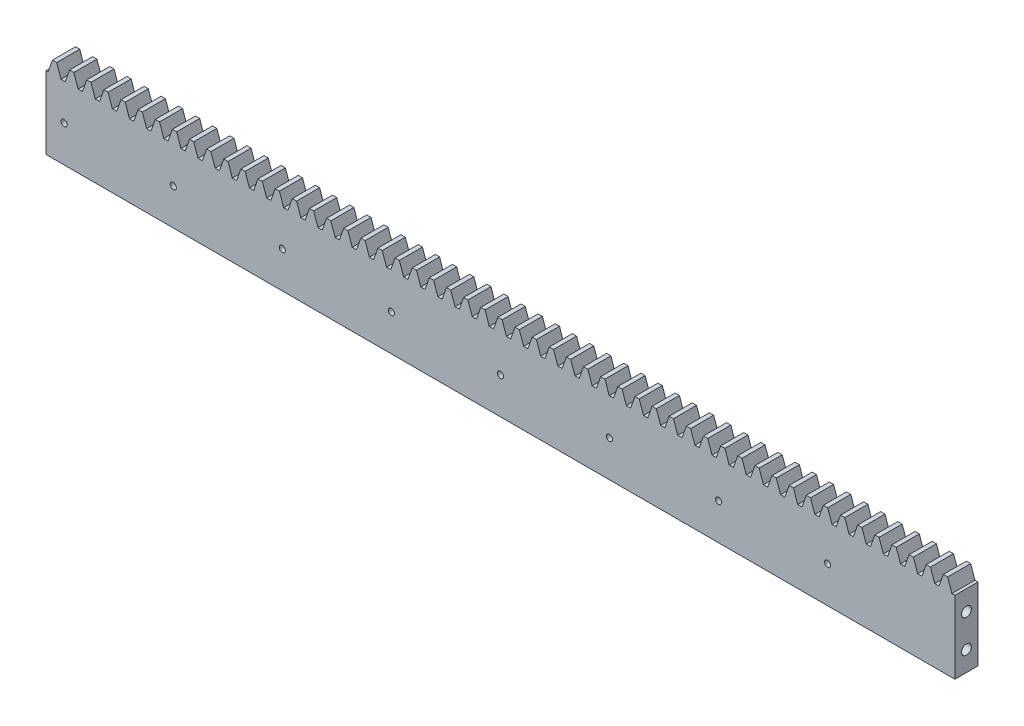
SolidWorks part; units mm, degrees
ref_plane "Front Plane" through (0, 0, 0) normal (0, 0, 1) x (1, 0, 0)
ref_plane "Top Plane" through (0, 0, 0) normal (0, 1, 0) x (1, 0, 0)
ref_plane "Right Plane" through (0, 0, 0) normal (1, 0, 0) x (0, 0, -1)
sketch "Original Sketch" plane through (0, 0, 0) normal (0, 0, 1) x (1, 0, 0)
  line L0 (5.3011, 16.625) -> (4.1236, 16.625) construction
  line L1 (4.1236, 16.625) -> (2.9446, 20) construction
  line L2 (2.9446, 20) -> (1.7677, 20) construction
  line L3 (1.7677, 20) -> (0.5887, 16.625) construction
  line L4 (0.5887, 16.625) -> (0, 16.625) construction
  line L5 (0, 16.625) -> (0, 0) construction
  line L6 (0, 0) -> (303, 0) construction
  line L7 (303, 0) -> (303, 18.9683) construction
  line L8 (303, 18.9683) -> (302.1814, 16.625) construction
  line L9 (302.1814, 16.625) -> (301.0039, 16.625) construction
  line L10 (301.0039, 16.625) -> (299.8249, 20) construction
  line L11 (299.8249, 20) -> (298.648, 20) construction
  line L12 (298.648, 20) -> (297.469, 16.625) construction
  line L13 (297.469, 16.625) -> (296.2915, 16.625) construction
  line L14 (296.2915, 16.625) -> (295.1125, 20) construction
  line L15 (295.1125, 20) -> (293.9356, 20) construction
  line L16 (293.9356, 20) -> (292.7566, 16.625) construction
  line L17 (292.7566, 16.625) -> (291.5791, 16.625) construction
  line L18 (291.5791, 16.625) -> (290.4001, 20) construction
  line L19 (290.4001, 20) -> (289.2232, 20) construction
  line L20 (289.2232, 20) -> (288.0442, 16.625) construction
  line L21 (288.0442, 16.625) -> (286.8667, 16.625) construction
  line L22 (286.8667, 16.625) -> (285.6877, 20) construction
  line L23 (285.6877, 20) -> (284.5109, 20) construction
  line L24 (284.5109, 20) -> (283.3318, 16.625) construction
  line L25 (283.3318, 16.625) -> (282.1544, 16.625) construction
  line L26 (282.1544, 16.625) -> (280.9753, 20) construction
  line L27 (280.9753, 20) -> (279.7985, 20) construction
  line L28 (279.7985, 20) -> (278.6195, 16.625) construction
  line L29 (278.6195, 16.625) -> (277.442, 16.625) construction
  line L30 (277.442, 16.625) -> (276.263, 20) construction
  line L31 (276.263, 20) -> (275.0861, 20) construction
  line L32 (275.0861, 20) -> (273.9071, 16.625) construction
  line L33 (273.9071, 16.625) -> (272.7296, 16.625) construction
  line L34 (272.7296, 16.625) -> (271.5506, 20) construction
  line L35 (271.5506, 20) -> (270.3737, 20) construction
  line L36 (270.3737, 20) -> (269.1947, 16.625) construction
  line L37 (269.1947, 16.625) -> (268.0172, 16.625) construction
  line L38 (268.0172, 16.625) -> (266.8382, 20) construction
  line L39 (266.8382, 20) -> (265.6613, 20) construction
  line L40 (265.6613, 20) -> (264.4823, 16.625) construction
  line L41 (264.4823, 16.625) -> (263.3048, 16.625) construction
  line L42 (263.3048, 16.625) -> (262.1258, 20) construction
  line L43 (262.1258, 20) -> (260.9489, 20) construction
  line L44 (260.9489, 20) -> (259.7699, 16.625) construction
  line L45 (259.7699, 16.625) -> (258.5924, 16.625) construction
  line L46 (258.5924, 16.625) -> (257.4134, 20) construction
  line L47 (257.4134, 20) -> (256.2365, 20) construction
  line L48 (256.2365, 20) -> (255.0575, 16.625) construction
  line L49 (255.0575, 16.625) -> (253.88, 16.625) construction
  line L50 (253.88, 16.625) -> (252.701, 20) construction
  line L51 (252.701, 20) -> (251.5242, 20) construction
  line L52 (251.5242, 20) -> (250.3452, 16.625) construction
  line L53 (250.3452, 16.625) -> (249.1677, 16.625) construction
  line L54 (249.1677, 16.625) -> (247.9887, 20) construction
  line L55 (247.9887, 20) -> (246.8118, 20) construction
  line L56 (246.8118, 20) -> (245.6328, 16.625) construction
  line L57 (245.6328, 16.625) -> (244.4553, 16.625) construction
  line L58 (244.4553, 16.625) -> (243.2763, 20) construction
  line L59 (243.2763, 20) -> (242.0994, 20) construction
  line L60 (242.0994, 20) -> (240.9204, 16.625) construction
  line L61 (240.9204, 16.625) -> (239.7429, 16.625) construction
  line L62 (239.7429, 16.625) -> (238.5639, 20) construction
  line L63 (238.5639, 20) -> (237.387, 20) construction
  line L64 (237.387, 20) -> (236.208, 16.625) construction
  line L65 (236.208, 16.625) -> (235.0305, 16.625) construction
  line L66 (235.0305, 16.625) -> (233.8515, 20) construction
  line L67 (233.8515, 20) -> (232.6746, 20) construction
  line L68 (232.6746, 20) -> (231.4956, 16.625) construction
  line L69 (231.4956, 16.625) -> (230.3181, 16.625) construction
  line L70 (230.3181, 16.625) -> (229.1391, 20) construction
  line L71 (229.1391, 20) -> (227.9622, 20) construction
  line L72 (227.9622, 20) -> (226.7832, 16.625) construction
  line L73 (226.7832, 16.625) -> (225.6057, 16.625) construction
  line L74 (225.6057, 16.625) -> (224.4267, 20) construction
  line L75 (224.4267, 20) -> (223.2498, 20) construction
  line L76 (223.2498, 20) -> (222.0708, 16.625) construction
  line L77 (222.0708, 16.625) -> (220.8933, 16.625) construction
  line L78 (220.8933, 16.625) -> (219.7143, 20) construction
  line L79 (219.7143, 20) -> (218.5375, 20) construction
  line L80 (218.5375, 20) -> (217.3585, 16.625) construction
  line L81 (217.3585, 16.625) -> (216.181, 16.625) construction
  line L82 (216.181, 16.625) -> (215.002, 20) construction
  line L83 (215.002, 20) -> (213.8251, 20) construction
  line L84 (213.8251, 20) -> (212.6461, 16.625) construction
  line L85 (212.6461, 16.625) -> (211.4686, 16.625) construction
  line L86 (211.4686, 16.625) -> (210.2896, 20) construction
  line L87 (210.2896, 20) -> (209.1127, 20) construction
  line L88 (209.1127, 20) -> (207.9337, 16.625) construction
  line L89 (207.9337, 16.625) -> (206.7562, 16.625) construction
  line L90 (206.7562, 16.625) -> (205.5772, 20) construction
  line L91 (205.5772, 20) -> (204.4003, 20) construction
  line L92 (204.4003, 20) -> (203.2213, 16.625) construction
  line L93 (203.2213, 16.625) -> (202.0438, 16.625) construction
  line L94 (202.0438, 16.625) -> (200.8648, 20) construction
  line L95 (200.8648, 20) -> (199.6879, 20) construction
  line L96 (199.6879, 20) -> (198.5089, 16.625) construction
  line L97 (198.5089, 16.625) -> (197.3314, 16.625) construction
  line L98 (197.3314, 16.625) -> (196.1524, 20) construction
  line L99 (196.1524, 20) -> (194.9755, 20) construction
  line L100 (194.9755, 20) -> (193.7965, 16.625) construction
  line L101 (193.7965, 16.625) -> (192.619, 16.625) construction
  line L102 (192.619, 16.625) -> (191.44, 20) construction
  line L103 (191.44, 20) -> (190.2631, 20) construction
  line L104 (190.2631, 20) -> (189.0841, 16.625) construction
  line L105 (189.0841, 16.625) -> (187.9067, 16.625) construction
  line L106 (187.9067, 16.625) -> (186.7276, 20) construction
  line L107 (186.7276, 20) -> (185.5508, 20) construction
  line L108 (185.5508, 20) -> (184.3718, 16.625) construction
  line L109 (184.3718, 16.625) -> (183.1943, 16.625) construction
  line L110 (183.1943, 16.625) -> (182.0153, 20) construction
  line L111 (182.0153, 20) -> (180.8384, 20) construction
  line L112 (180.8384, 20) -> (179.6594, 16.625) construction
  line L113 (179.6594, 16.625) -> (178.4819, 16.625) construction
  line L114 (178.4819, 16.625) -> (177.3029, 20) construction
  line L115 (177.3029, 20) -> (176.126, 20) construction
  line L116 (176.126, 20) -> (174.947, 16.625) construction
  line L117 (174.947, 16.625) -> (173.7695, 16.625) construction
  line L118 (173.7695, 16.625) -> (172.5905, 20) construction
  line L119 (172.5905, 20) -> (171.4136, 20) construction
  line L120 (171.4136, 20) -> (170.2346, 16.625) construction
  line L121 (170.2346, 16.625) -> (169.0571, 16.625) construction
  line L122 (169.0571, 16.625) -> (167.8781, 20) construction
  line L123 (167.8781, 20) -> (166.7012, 20) construction
  line L124 (166.7012, 20) -> (165.5222, 16.625) construction
  line L125 (165.5222, 16.625) -> (164.3447, 16.625) construction
  line L126 (164.3447, 16.625) -> (163.1657, 20) construction
  line L127 (163.1657, 20) -> (161.9888, 20) construction
  line L128 (161.9888, 20) -> (160.8098, 16.625) construction
  line L129 (160.8098, 16.625) -> (159.6323, 16.625) construction
  line L130 (159.6323, 16.625) -> (158.4533, 20) construction
  line L131 (158.4533, 20) -> (157.2765, 20) construction
  line L132 (157.2765, 20) -> (156.0975, 16.625) construction
  line L133 (156.0975, 16.625) -> (154.92, 16.625) construction
  line L134 (154.92, 16.625) -> (153.741, 20) construction
  line L135 (153.741, 20) -> (152.5641, 20) construction
  line L136 (152.5641, 20) -> (151.3851, 16.625) construction
  line L137 (151.3851, 16.625) -> (150.2076, 16.625) construction
  line L138 (150.2076, 16.625) -> (149.0286, 20) construction
  line L139 (149.0286, 20) -> (147.8517, 20) construction
  line L140 (147.8517, 20) -> (146.6727, 16.625) construction
  line L141 (146.6727, 16.625) -> (145.4952, 16.625) construction
  line L142 (145.4952, 16.625) -> (144.3162, 20) construction
  line L143 (144.3162, 20) -> (143.1393, 20) construction
  line L144 (143.1393, 20) -> (141.9603, 16.625) construction
  line L145 (141.9603, 16.625) -> (140.7828, 16.625) construction
  line L146 (140.7828, 16.625) -> (139.6038, 20) construction
  line L147 (139.6038, 20) -> (138.4269, 20) construction
  line L148 (138.4269, 20) -> (137.2479, 16.625) construction
  line L149 (137.2479, 16.625) -> (136.0704, 16.625) construction
  line L150 (136.0704, 16.625) -> (134.8914, 20) construction
  line L151 (134.8914, 20) -> (133.7145, 20) construction
  line L152 (133.7145, 20) -> (132.5355, 16.625) construction
  line L153 (132.5355, 16.625) -> (131.358, 16.625) construction
  line L154 (131.358, 16.625) -> (130.179, 20) construction
  line L155 (130.179, 20) -> (129.0021, 20) construction
  line L156 (129.0021, 20) -> (127.8231, 16.625) construction
  line L157 (127.8231, 16.625) -> (126.6456, 16.625) construction
  line L158 (126.6456, 16.625) -> (125.4666, 20) construction
  line L159 (125.4666, 20) -> (124.2898, 20) construction
  line L160 (124.2898, 20) -> (123.1108, 16.625) construction
  line L161 (123.1108, 16.625) -> (121.9333, 16.625) construction
  line L162 (121.9333, 16.625) -> (120.7543, 20) construction
  line L163 (120.7543, 20) -> (119.5774, 20) construction
  line L164 (119.5774, 20) -> (118.3984, 16.625) construction
  line L165 (118.3984, 16.625) -> (117.2209, 16.625) construction
  line L166 (117.2209, 16.625) -> (116.0419, 20) construction
  line L167 (116.0419, 20) -> (114.865, 20) construction
  line L168 (114.865, 20) -> (113.686, 16.625) construction
  line L169 (113.686, 16.625) -> (112.5085, 16.625) construction
  line L170 (112.5085, 16.625) -> (111.3295, 20) construction
  line L171 (111.3295, 20) -> (110.1526, 20) construction
  line L172 (110.1526, 20) -> (108.9736, 16.625) construction
  line L173 (108.9736, 16.625) -> (107.7961, 16.625) construction
  line L174 (107.7961, 16.625) -> (106.6171, 20) construction
  line L175 (106.6171, 20) -> (105.4402, 20) construction
  line L176 (105.4402, 20) -> (104.2612, 16.625) construction
  line L177 (104.2612, 16.625) -> (103.0837, 16.625) construction
  line L178 (103.0837, 16.625) -> (101.9047, 20) construction
  line L179 (101.9047, 20) -> (100.7278, 20) construction
  line L180 (100.7278, 20) -> (99.5488, 16.625) construction
  line L181 (99.5488, 16.625) -> (98.3713, 16.625) construction
  line L182 (98.3713, 16.625) -> (97.1923, 20) construction
  line L183 (97.1923, 20) -> (96.0155, 20) construction
  line L184 (96.0155, 20) -> (94.8364, 16.625) construction
  line L185 (94.8364, 16.625) -> (93.659, 16.625) construction
  line L186 (93.659, 16.625) -> (92.48, 20) construction
  line L187 (92.48, 20) -> (91.3031, 20) construction
  line L188 (91.3031, 20) -> (90.1241, 16.625) construction
  line L189 (90.1241, 16.625) -> (88.9466, 16.625) construction
  line L190 (88.9466, 16.625) -> (87.7676, 20) construction
  line L191 (87.7676, 20) -> (86.5907, 20) construction
  line L192 (86.5907, 20) -> (85.4117, 16.625) construction
  line L193 (85.4117, 16.625) -> (84.2342, 16.625) construction
  line L194 (84.2342, 16.625) -> (83.0552, 20) construction
  line L195 (83.0552, 20) -> (81.8783, 20) construction
  line L196 (81.8783, 20) -> (80.6993, 16.625) construction
  line L197 (80.6993, 16.625) -> (79.5218, 16.625) construction
  line L198 (79.5218, 16.625) -> (78.3428, 20) construction
  line L199 (78.3428, 20) -> (77.1659, 20) construction
  line L200 (77.1659, 20) -> (75.9869, 16.625) construction
  line L201 (75.9869, 16.625) -> (74.8094, 16.625) construction
  line L202 (74.8094, 16.625) -> (73.6304, 20) construction
  line L203 (73.6304, 20) -> (72.4535, 20) construction
  line L204 (72.4535, 20) -> (71.2745, 16.625) construction
  line L205 (71.2745, 16.625) -> (70.097, 16.625) construction
  line L206 (70.097, 16.625) -> (68.918, 20) construction
  line L207 (68.918, 20) -> (67.7411, 20) construction
  line L208 (67.7411, 20) -> (66.5621, 16.625) construction
  line L209 (66.5621, 16.625) -> (65.3846, 16.625) construction
  line L210 (65.3846, 16.625) -> (64.2056, 20) construction
  line L211 (64.2056, 20) -> (63.0288, 20) construction
  line L212 (63.0288, 20) -> (61.8498, 16.625) construction
  line L213 (61.8498, 16.625) -> (60.6723, 16.625) construction
  line L214 (60.6723, 16.625) -> (59.4933, 20) construction
  line L215 (59.4933, 20) -> (58.3164, 20) construction
  line L216 (58.3164, 20) -> (57.1374, 16.625) construction
  line L217 (57.1374, 16.625) -> (55.9599, 16.625) construction
  line L218 (55.9599, 16.625) -> (54.7809, 20) construction
  line L219 (54.7809, 20) -> (53.604, 20) construction
  line L220 (53.604, 20) -> (52.425, 16.625) construction
  line L221 (52.425, 16.625) -> (51.2475, 16.625) construction
  line L222 (51.2475, 16.625) -> (50.0685, 20) construction
  line L223 (50.0685, 20) -> (48.8916, 20) construction
  line L224 (48.8916, 20) -> (47.7126, 16.625) construction
  line L225 (47.7126, 16.625) -> (46.5351, 16.625) construction
  line L226 (46.5351, 16.625) -> (45.3561, 20) construction
  line L227 (45.3561, 20) -> (44.1792, 20) construction
  line L228 (44.1792, 20) -> (43.0002, 16.625) construction
  line L229 (43.0002, 16.625) -> (41.8227, 16.625) construction
  line L230 (41.8227, 16.625) -> (40.6437, 20) construction
  line L231 (40.6437, 20) -> (39.4668, 20) construction
  line L232 (39.4668, 20) -> (38.2878, 16.625) construction
  line L233 (38.2878, 16.625) -> (37.1103, 16.625) construction
  line L234 (37.1103, 16.625) -> (35.9313, 20) construction
  line L235 (35.9313, 20) -> (34.7544, 20) construction
  line L236 (34.7544, 20) -> (33.5754, 16.625) construction
  line L237 (33.5754, 16.625) -> (32.3979, 16.625) construction
  line L238 (32.3979, 16.625) -> (31.2189, 20) construction
  line L239 (31.2189, 20) -> (30.0421, 20) construction
  line L240 (30.0421, 20) -> (28.8631, 16.625) construction
  line L241 (28.8631, 16.625) -> (27.6856, 16.625) construction
  line L242 (27.6856, 16.625) -> (26.5066, 20) construction
  line L243 (26.5066, 20) -> (25.3297, 20) construction
  line L244 (25.3297, 20) -> (24.1507, 16.625) construction
  line L245 (24.1507, 16.625) -> (22.9732, 16.625) construction
  line L246 (22.9732, 16.625) -> (21.7942, 20) construction
  line L247 (21.7942, 20) -> (20.6173, 20) construction
  line L248 (20.6173, 20) -> (19.4383, 16.625) construction
  line L249 (19.4383, 16.625) -> (18.2608, 16.625) construction
  line L250 (18.2608, 16.625) -> (17.0818, 20) construction
  line L251 (17.0818, 20) -> (15.9049, 20) construction
  line L252 (15.9049, 20) -> (14.7259, 16.625) construction
  line L253 (14.7259, 16.625) -> (13.5484, 16.625) construction
  line L254 (13.5484, 16.625) -> (12.3694, 20) construction
  line L255 (12.3694, 20) -> (11.1925, 20) construction
  line L256 (11.1925, 20) -> (10.0135, 16.625) construction
  line L257 (10.0135, 16.625) -> (8.836, 16.625) construction
  line L258 (8.836, 16.625) -> (7.657, 20) construction
  line L259 (7.657, 20) -> (6.4801, 20) construction
  line L260 (6.4801, 20) -> (5.3011, 16.625) construction
sketch "Sketch6" plane through (0, 0, 0) normal (0, 0, 1) x (1, 0, 0)
  line L2 (303, 0) -> (303, 18.9683) construction
  line L3 (303, 18.9683) -> (302.1814, 16.625) construction
  line L4 (302.1814, 16.625) -> (301.0039, 16.625) construction
  line L5 (301.0039, 16.625) -> (299.8249, 20) construction
  line L6 (299.8249, 20) -> (298.648, 20) construction
  line L7 (298.648, 20) -> (297.469, 16.625) construction
  line L8 (297.469, 16.625) -> (296.2915, 16.625) construction
  line L9 (296.2915, 16.625) -> (295.1125, 20) construction
  line L10 (295.1125, 20) -> (293.9356, 20) construction
  line L11 (293.9356, 20) -> (292.7566, 16.625) construction
  line L12 (292.7566, 16.625) -> (291.5791, 16.625) construction
  line L13 (291.5791, 16.625) -> (290.4001, 20) construction
  line L14 (290.4001, 20) -> (289.2232, 20) construction
  line L15 (289.2232, 20) -> (288.0442, 16.625) construction
  line L16 (288.0442, 16.625) -> (286.8667, 16.625) construction
  line L17 (286.8667, 16.625) -> (285.6877, 20) construction
  line L18 (285.6877, 20) -> (284.5109, 20) construction
  line L19 (284.5109, 20) -> (283.3318, 16.625) construction
  line L20 (283.3318, 16.625) -> (282.1544, 16.625) construction
  line L21 (282.1544, 16.625) -> (280.9753, 20) construction
  line L22 (280.9753, 20) -> (279.7985, 20) construction
  line L23 (279.7985, 20) -> (278.6195, 16.625) construction
  line L24 (278.6195, 16.625) -> (277.442, 16.625) construction
  line L25 (277.442, 16.625) -> (276.263, 20) construction
  line L26 (276.263, 20) -> (275.0861, 20) construction
  line L27 (275.0861, 20) -> (273.9071, 16.625) construction
  line L28 (273.9071, 16.625) -> (272.7296, 16.625) construction
  line L29 (272.7296, 16.625) -> (271.5506, 20) construction
  line L30 (271.5506, 20) -> (270.3737, 20) construction
  line L31 (270.3737, 20) -> (269.1947, 16.625) construction
  line L32 (269.1947, 16.625) -> (268.0172, 16.625) construction
  line L33 (268.0172, 16.625) -> (266.8382, 20) construction
  line L34 (266.8382, 20) -> (265.6613, 20) construction
  line L35 (265.6613, 20) -> (264.4823, 16.625) construction
  line L36 (264.4823, 16.625) -> (263.3048, 16.625) construction
  line L37 (263.3048, 16.625) -> (262.1258, 20) construction
  line L38 (262.1258, 20) -> (260.9489, 20) construction
  line L39 (260.9489, 20) -> (259.7699, 16.625) construction
  line L40 (259.7699, 16.625) -> (258.5924, 16.625) construction
  line L41 (258.5924, 16.625) -> (257.4134, 20) construction
  line L42 (257.4134, 20) -> (256.2365, 20) construction
  line L43 (256.2365, 20) -> (255.0575, 16.625) construction
  line L44 (255.0575, 16.625) -> (253.88, 16.625) construction
  line L45 (253.88, 16.625) -> (252.701, 20) construction
  line L46 (252.701, 20) -> (251.5242, 20) construction
  line L47 (251.5242, 20) -> (250.3452, 16.625) construction
  line L48 (250.3452, 16.625) -> (249.1677, 16.625) construction
  line L49 (249.1677, 16.625) -> (247.9887, 20) construction
  line L50 (247.9887, 20) -> (246.8118, 20) construction
  line L51 (246.8118, 20) -> (245.6328, 16.625) construction
  line L52 (245.6328, 16.625) -> (244.4553, 16.625) construction
  line L53 (244.4553, 16.625) -> (243.2763, 20) construction
  line L54 (243.2763, 20) -> (242.0994, 20) construction
  line L55 (242.0994, 20) -> (240.9204, 16.625) construction
  line L56 (240.9204, 16.625) -> (239.7429, 16.625) construction
  line L57 (239.7429, 16.625) -> (238.5639, 20) construction
  line L58 (238.5639, 20) -> (237.387, 20) construction
  line L59 (237.387, 20) -> (236.208, 16.625) construction
  line L60 (236.208, 16.625) -> (235.0305, 16.625) construction
  line L61 (235.0305, 16.625) -> (233.8515, 20) construction
  line L62 (233.8515, 20) -> (232.6746, 20) construction
  line L63 (232.6746, 20) -> (231.4956, 16.625) construction
  line L64 (231.4956, 16.625) -> (230.3181, 16.625) construction
  line L65 (230.3181, 16.625) -> (229.1391, 20) construction
  line L66 (229.1391, 20) -> (227.9622, 20) construction
  line L67 (227.9622, 20) -> (226.7832, 16.625) construction
  line L68 (226.7832, 16.625) -> (225.6057, 16.625) construction
  line L69 (225.6057, 16.625) -> (224.4267, 20) construction
  line L70 (224.4267, 20) -> (223.2498, 20) construction
  line L71 (223.2498, 20) -> (222.0708, 16.625) construction
  line L72 (222.0708, 16.625) -> (220.8933, 16.625) construction
  line L73 (220.8933, 16.625) -> (219.7143, 20) construction
  line L74 (219.7143, 20) -> (218.5375, 20) construction
  line L75 (218.5375, 20) -> (217.3585, 16.625) construction
  line L76 (217.3585, 16.625) -> (216.181, 16.625) construction
  line L77 (216.181, 16.625) -> (215.002, 20) construction
  line L78 (215.002, 20) -> (213.8251, 20) construction
  line L79 (213.8251, 20) -> (212.6461, 16.625) construction
  line L80 (212.6461, 16.625) -> (211.4686, 16.625) construction
  line L81 (211.4686, 16.625) -> (210.2896, 20) construction
  line L82 (210.2896, 20) -> (209.1127, 20) construction
  line L83 (209.1127, 20) -> (207.9337, 16.625) construction
  line L84 (207.9337, 16.625) -> (206.7562, 16.625) construction
  line L85 (206.7562, 16.625) -> (205.5772, 20) construction
  line L86 (205.5772, 20) -> (204.4003, 20) construction
  line L87 (204.4003, 20) -> (203.2213, 16.625) construction
  line L88 (203.2213, 16.625) -> (202.0438, 16.625) construction
  line L89 (202.0438, 16.625) -> (200.8648, 20) construction
  line L90 (200.8648, 20) -> (199.6879, 20) construction
  line L91 (199.6879, 20) -> (198.5089, 16.625) construction
  line L92 (198.5089, 16.625) -> (197.3314, 16.625) construction
  line L93 (197.3314, 16.625) -> (196.1524, 20) construction
  line L94 (196.1524, 20) -> (194.9755, 20) construction
  line L95 (194.9755, 20) -> (193.7965, 16.625) construction
  line L96 (193.7965, 16.625) -> (192.619, 16.625) construction
  line L97 (192.619, 16.625) -> (191.44, 20) construction
  line L98 (191.44, 20) -> (190.2631, 20) construction
  line L99 (190.2631, 20) -> (189.0841, 16.625) construction
  line L100 (189.0841, 16.625) -> (187.9067, 16.625) construction
  line L101 (187.9067, 16.625) -> (186.7276, 20) construction
  line L102 (186.7276, 20) -> (185.5508, 20) construction
  line L103 (185.5508, 20) -> (184.3718, 16.625) construction
  line L104 (184.3718, 16.625) -> (183.1943, 16.625) construction
  line L105 (183.1943, 16.625) -> (182.0153, 20) construction
  line L106 (182.0153, 20) -> (180.8384, 20) construction
  line L107 (180.8384, 20) -> (179.6594, 16.625) construction
  line L108 (179.6594, 16.625) -> (178.4819, 16.625) construction
  line L109 (178.4819, 16.625) -> (177.3029, 20) construction
  line L110 (177.3029, 20) -> (176.126, 20) construction
  line L111 (176.126, 20) -> (174.947, 16.625) construction
  line L112 (174.947, 16.625) -> (173.7695, 16.625) construction
  line L113 (173.7695, 16.625) -> (172.5905, 20) construction
  line L114 (172.5905, 20) -> (171.4136, 20) construction
  line L115 (171.4136, 20) -> (170.2346, 16.625) construction
  line L116 (170.2346, 16.625) -> (169.0571, 16.625) construction
  line L117 (169.0571, 16.625) -> (167.8781, 20) construction
  line L118 (167.8781, 20) -> (166.7012, 20) construction
  line L119 (166.7012, 20) -> (165.5222, 16.625) construction
  line L120 (165.5222, 16.625) -> (164.3447, 16.625) construction
  line L121 (164.3447, 16.625) -> (163.1657, 20) construction
  line L122 (163.1657, 20) -> (161.9888, 20) construction
  line L123 (161.9888, 20) -> (160.8098, 16.625) construction
  line L124 (160.8098, 16.625) -> (159.6323, 16.625) construction
  line L125 (159.6323, 16.625) -> (158.4533, 20) construction
  line L126 (158.4533, 20) -> (157.2765, 20) construction
  line L127 (157.2765, 20) -> (156.0975, 16.625) construction
  line L128 (156.0975, 16.625) -> (154.92, 16.625) construction
  line L129 (154.92, 16.625) -> (153.741, 20) construction
  line L130 (153.741, 20) -> (152.5641, 20) construction
  line L131 (152.5641, 20) -> (151.3851, 16.625) construction
  line L132 (151.3851, 16.625) -> (150.2076, 16.625) construction
  line L133 (150.2076, 16.625) -> (149.0286, 20) construction
  line L134 (149.0286, 20) -> (147.8517, 20) construction
  line L135 (147.8517, 20) -> (146.6727, 16.625) construction
  line L136 (146.6727, 16.625) -> (145.4952, 16.625) construction
  line L137 (145.4952, 16.625) -> (144.3162, 20) construction
  line L138 (144.3162, 20) -> (143.1393, 20) construction
  line L139 (143.1393, 20) -> (141.9603, 16.625) construction
  line L140 (141.9603, 16.625) -> (140.7828, 16.625) construction
  line L141 (140.7828, 16.625) -> (139.6038, 20) construction
  line L142 (139.6038, 20) -> (138.4269, 20) construction
  line L143 (138.4269, 20) -> (137.2479, 16.625) construction
  line L144 (137.2479, 16.625) -> (136.0704, 16.625) construction
  line L145 (136.0704, 16.625) -> (134.8914, 20) construction
  line L146 (134.8914, 20) -> (133.7145, 20) construction
  line L147 (133.7145, 20) -> (132.5355, 16.625) construction
  line L148 (132.5355, 16.625) -> (131.358, 16.625) construction
  line L149 (131.358, 16.625) -> (130.179, 20) construction
  line L150 (130.179, 20) -> (129.0021, 20) construction
  line L151 (129.0021, 20) -> (127.8231, 16.625) construction
  line L152 (127.8231, 16.625) -> (126.6456, 16.625) construction
  line L153 (126.6456, 16.625) -> (125.4666, 20) construction
  line L154 (125.4666, 20) -> (124.2898, 20) construction
  line L155 (124.2898, 20) -> (123.1108, 16.625) construction
  line L156 (123.1108, 16.625) -> (121.9333, 16.625) construction
  line L157 (121.9333, 16.625) -> (120.7543, 20) construction
  line L158 (120.7543, 20) -> (119.5774, 20) construction
  line L159 (119.5774, 20) -> (118.3984, 16.625) construction
  line L160 (118.3984, 16.625) -> (117.2209, 16.625) construction
  line L161 (117.2209, 16.625) -> (116.0419, 20) construction
  line L162 (116.0419, 20) -> (114.865, 20) construction
  line L163 (114.865, 20) -> (113.686, 16.625) construction
  line L164 (113.686, 16.625) -> (112.5085, 16.625) construction
  line L165 (112.5085, 16.625) -> (111.3295, 20) construction
  line L166 (111.3295, 20) -> (110.1526, 20) construction
  line L167 (110.1526, 20) -> (108.9736, 16.625) construction
  line L168 (108.9736, 16.625) -> (107.7961, 16.625) construction
  line L169 (107.7961, 16.625) -> (106.6171, 20) construction
  line L170 (106.6171, 20) -> (105.4402, 20) construction
  line L171 (105.4402, 20) -> (104.2612, 16.625) construction
  line L172 (104.2612, 16.625) -> (103.0837, 16.625) construction
  line L173 (103.0837, 16.625) -> (101.9047, 20) construction
  line L174 (101.9047, 20) -> (100.7278, 20) construction
  line L175 (100.7278, 20) -> (99.5488, 16.625) construction
  line L176 (99.5488, 16.625) -> (98.3713, 16.625) construction
  line L177 (98.3713, 16.625) -> (97.1923, 20) construction
  line L178 (97.1923, 20) -> (96.0155, 20) construction
  line L179 (96.0155, 20) -> (94.8364, 16.625) construction
  line L180 (94.8364, 16.625) -> (93.659, 16.625) construction
  line L181 (93.659, 16.625) -> (92.48, 20) construction
  line L182 (92.48, 20) -> (91.3031, 20) construction
  line L183 (91.3031, 20) -> (90.1241, 16.625) construction
  line L184 (90.1241, 16.625) -> (88.9466, 16.625) construction
  line L185 (88.9466, 16.625) -> (87.7676, 20) construction
  line L186 (87.7676, 20) -> (86.5907, 20) construction
  line L187 (86.5907, 20) -> (85.4117, 16.625) construction
  line L188 (85.4117, 16.625) -> (84.2342, 16.625) construction
  line L189 (84.2342, 16.625) -> (83.0552, 20) construction
  line L190 (83.0552, 20) -> (81.8783, 20) construction
  line L191 (81.8783, 20) -> (80.6993, 16.625) construction
  line L192 (80.6993, 16.625) -> (79.5218, 16.625) construction
  line L193 (79.5218, 16.625) -> (78.3428, 20) construction
  line L194 (78.3428, 20) -> (77.1659, 20) construction
  line L195 (77.1659, 20) -> (75.9869, 16.625) construction
  line L196 (75.9869, 16.625) -> (74.8094, 16.625) construction
  line L197 (74.8094, 16.625) -> (73.6304, 20) construction
  line L198 (73.6304, 20) -> (72.4535, 20) construction
  line L199 (72.4535, 20) -> (71.2745, 16.625) construction
  line L200 (71.2745, 16.625) -> (70.097, 16.625) construction
  line L201 (70.097, 16.625) -> (68.918, 20) construction
  line L202 (68.918, 20) -> (67.7411, 20) construction
  line L203 (67.7411, 20) -> (66.5621, 16.625) construction
  line L204 (66.5621, 16.625) -> (65.3846, 16.625) construction
  line L205 (65.3846, 16.625) -> (64.2056, 20) construction
  line L206 (64.2056, 20) -> (63.0288, 20) construction
  line L207 (63.0288, 20) -> (61.8498, 16.625) construction
  line L208 (61.8498, 16.625) -> (60.6723, 16.625) construction
  line L209 (60.6723, 16.625) -> (59.4933, 20) construction
  line L210 (59.4933, 20) -> (58.3164, 20) construction
  line L211 (58.3164, 20) -> (57.1374, 16.625) construction
  line L212 (57.1374, 16.625) -> (55.9599, 16.625) construction
  line L213 (55.9599, 16.625) -> (54.7809, 20) construction
  line L214 (54.7809, 20) -> (53.604, 20) construction
  line L215 (53.604, 20) -> (52.425, 16.625) construction
  line L216 (52.425, 16.625) -> (51.2475, 16.625) construction
  line L217 (51.2475, 16.625) -> (50.0685, 20) construction
  line L218 (50.0685, 20) -> (48.8916, 20) construction
  line L219 (48.8916, 20) -> (47.7126, 16.625) construction
  line L220 (47.7126, 16.625) -> (46.5351, 16.625) construction
  line L221 (46.5351, 16.625) -> (45.3561, 20) construction
  line L222 (45.3561, 20) -> (44.1792, 20) construction
  line L223 (44.1792, 20) -> (43.0002, 16.625) construction
  line L224 (43.0002, 16.625) -> (41.8227, 16.625) construction
  line L225 (41.8227, 16.625) -> (40.6437, 20) construction
  line L226 (40.6437, 20) -> (39.4668, 20) construction
  line L227 (39.4668, 20) -> (38.2878, 16.625) construction
  line L228 (38.2878, 16.625) -> (37.1103, 16.625) construction
  line L229 (37.1103, 16.625) -> (35.9313, 20) construction
  line L230 (35.9313, 20) -> (34.7544, 20) construction
  line L231 (34.7544, 20) -> (33.5754, 16.625) construction
  line L232 (33.5754, 16.625) -> (32.3979, 16.625) construction
  line L233 (32.3979, 16.625) -> (31.2189, 20) construction
  line L234 (31.2189, 20) -> (30.0421, 20) construction
  line L235 (30.0421, 20) -> (28.8631, 16.625) construction
  line L236 (28.8631, 16.625) -> (27.6856, 16.625) construction
  line L237 (27.6856, 16.625) -> (26.5066, 20) construction
  line L238 (26.5066, 20) -> (25.3297, 20) construction
  line L239 (25.3297, 20) -> (24.1507, 16.625) construction
  line L240 (24.1507, 16.625) -> (22.9732, 16.625) construction
  line L241 (22.9732, 16.625) -> (21.7942, 20) construction
  line L242 (21.7942, 20) -> (20.6173, 20) construction
  line L243 (20.6173, 20) -> (19.4383, 16.625) construction
  line L244 (19.4383, 16.625) -> (18.2608, 16.625) construction
  line L245 (18.2608, 16.625) -> (17.0818, 20) construction
  line L246 (17.0818, 20) -> (15.9049, 20) construction
  line L247 (15.9049, 20) -> (14.7259, 16.625) construction
  line L248 (14.7259, 16.625) -> (13.5484, 16.625) construction
  line L249 (13.5484, 16.625) -> (12.3694, 20) construction
  line L250 (12.3694, 20) -> (11.1925, 20) construction
  line L251 (11.1925, 20) -> (10.0135, 16.625) construction
  line L252 (10.0135, 16.625) -> (8.836, 16.625) construction
  line L253 (8.836, 16.625) -> (7.657, 20) construction
  line L254 (7.657, 20) -> (6.4801, 20) construction
  line L255 (6.4801, 20) -> (5.3011, 16.625) construction
  line L256 (5.3011, 16.625) -> (4.1236, 16.625) construction
  line L257 (4.1236, 16.625) -> (2.9446, 20) construction
  line L258 (2.9446, 20) -> (1.7677, 20) construction
  line L259 (1.7677, 20) -> (0.5887, 16.625) construction
  line L260 (0.5887, 16.625) -> (0, 16.625) construction
  line L263 (303, 0) -> (303, 18.9683)
  line L264 (303, 18.9683) -> (302.1814, 16.625)
  line L265 (302.1814, 16.625) -> (301.0039, 16.625)
  line L266 (301.0039, 16.625) -> (299.8249, 20)
  line L267 (299.8249, 20) -> (298.648, 20)
  line L268 (298.648, 20) -> (297.469, 16.625)
  line L269 (297.469, 16.625) -> (296.2915, 16.625)
  line L270 (296.2915, 16.625) -> (295.1125, 20)
  line L271 (295.1125, 20) -> (293.9356, 20)
  line L272 (293.9356, 20) -> (292.7566, 16.625)
  line L273 (292.7566, 16.625) -> (291.5791, 16.625)
  line L274 (291.5791, 16.625) -> (290.4001, 20)
  line L275 (290.4001, 20) -> (289.2232, 20)
  line L276 (289.2232, 20) -> (288.0442, 16.625)
  line L277 (288.0442, 16.625) -> (286.8667, 16.625)
  line L278 (286.8667, 16.625) -> (285.6877, 20)
  line L279 (285.6877, 20) -> (284.5109, 20)
  line L280 (284.5109, 20) -> (283.3318, 16.625)
  line L281 (283.3318, 16.625) -> (282.1544, 16.625)
  line L282 (282.1544, 16.625) -> (280.9753, 20)
  line L283 (280.9753, 20) -> (279.7985, 20)
  line L284 (279.7985, 20) -> (278.6195, 16.625)
  line L285 (278.6195, 16.625) -> (277.442, 16.625)
  line L286 (277.442, 16.625) -> (276.263, 20)
  line L287 (276.263, 20) -> (275.0861, 20)
  line L288 (275.0861, 20) -> (273.9071, 16.625)
  line L289 (273.9071, 16.625) -> (272.7296, 16.625)
  line L290 (272.7296, 16.625) -> (271.5506, 20)
  line L291 (271.5506, 20) -> (270.3737, 20)
  line L292 (270.3737, 20) -> (269.1947, 16.625)
  line L293 (269.1947, 16.625) -> (268.0172, 16.625)
  line L294 (268.0172, 16.625) -> (266.8382, 20)
  line L295 (266.8382, 20) -> (265.6613, 20)
  line L296 (265.6613, 20) -> (264.4823, 16.625)
  line L297 (264.4823, 16.625) -> (263.3048, 16.625)
  line L298 (263.3048, 16.625) -> (262.1258, 20)
  line L299 (262.1258, 20) -> (260.9489, 20)
  line L300 (260.9489, 20) -> (259.7699, 16.625)
  line L301 (259.7699, 16.625) -> (258.5924, 16.625)
  line L302 (258.5924, 16.625) -> (257.4134, 20)
  line L303 (257.4134, 20) -> (256.2365, 20)
  line L304 (256.2365, 20) -> (255.0575, 16.625)
  line L305 (255.0575, 16.625) -> (253.88, 16.625)
  line L306 (253.88, 16.625) -> (252.701, 20)
  line L307 (252.701, 20) -> (251.5242, 20)
  line L308 (251.5242, 20) -> (250.3452, 16.625)
  line L309 (250.3452, 16.625) -> (249.1677, 16.625)
  line L310 (249.1677, 16.625) -> (247.9887, 20)
  line L311 (247.9887, 20) -> (246.8118, 20)
  line L312 (246.8118, 20) -> (245.6328, 16.625)
  line L313 (245.6328, 16.625) -> (244.4553, 16.625)
  line L314 (244.4553, 16.625) -> (243.2763, 20)
  line L315 (243.2763, 20) -> (242.0994, 20)
  line L316 (242.0994, 20) -> (240.9204, 16.625)
  line L317 (240.9204, 16.625) -> (239.7429, 16.625)
  line L318 (239.7429, 16.625) -> (238.5639, 20)
  line L319 (238.5639, 20) -> (237.387, 20)
  line L320 (237.387, 20) -> (236.208, 16.625)
  line L321 (236.208, 16.625) -> (235.0305, 16.625)
  line L322 (235.0305, 16.625) -> (233.8515, 20)
  line L323 (233.8515, 20) -> (232.6746, 20)
  line L324 (232.6746, 20) -> (231.4956, 16.625)
  line L325 (231.4956, 16.625) -> (230.3181, 16.625)
  line L326 (230.3181, 16.625) -> (229.1391, 20)
  line L327 (229.1391, 20) -> (227.9622, 20)
  line L328 (227.9622, 20) -> (226.7832, 16.625)
  line L329 (226.7832, 16.625) -> (225.6057, 16.625)
  line L330 (225.6057, 16.625) -> (224.4267, 20)
  line L331 (224.4267, 20) -> (223.2498, 20)
  line L332 (223.2498, 20) -> (222.0708, 16.625)
  line L333 (222.0708, 16.625) -> (220.8933, 16.625)
  line L334 (220.8933, 16.625) -> (219.7143, 20)
  line L335 (219.7143, 20) -> (218.5375, 20)
  line L336 (218.5375, 20) -> (217.3585, 16.625)
  line L337 (217.3585, 16.625) -> (216.181, 16.625)
  line L338 (216.181, 16.625) -> (215.002, 20)
  line L339 (215.002, 20) -> (213.8251, 20)
  line L340 (213.8251, 20) -> (212.6461, 16.625)
  line L341 (212.6461, 16.625) -> (211.4686, 16.625)
  line L342 (211.4686, 16.625) -> (210.2896, 20)
  line L343 (210.2896, 20) -> (209.1127, 20)
  line L344 (209.1127, 20) -> (207.9337, 16.625)
  line L345 (207.9337, 16.625) -> (206.7562, 16.625)
  line L346 (206.7562, 16.625) -> (205.5772, 20)
  line L347 (205.5772, 20) -> (204.4003, 20)
  line L348 (204.4003, 20) -> (203.2213, 16.625)
  line L349 (203.2213, 16.625) -> (202.0438, 16.625)
  line L350 (202.0438, 16.625) -> (200.8648, 20)
  line L351 (200.8648, 20) -> (199.6879, 20)
  line L352 (199.6879, 20) -> (198.5089, 16.625)
  line L353 (198.5089, 16.625) -> (197.3314, 16.625)
  line L354 (197.3314, 16.625) -> (196.1524, 20)
  line L355 (196.1524, 20) -> (194.9755, 20)
  line L356 (194.9755, 20) -> (193.7965, 16.625)
  line L357 (193.7965, 16.625) -> (192.619, 16.625)
  line L358 (192.619, 16.625) -> (191.44, 20)
  line L359 (191.44, 20) -> (190.2631, 20)
  line L360 (190.2631, 20) -> (189.0841, 16.625)
  line L361 (189.0841, 16.625) -> (187.9067, 16.625)
  line L362 (187.9067, 16.625) -> (186.7276, 20)
  line L363 (186.7276, 20) -> (185.5508, 20)
  line L364 (185.5508, 20) -> (184.3718, 16.625)
  line L365 (184.3718, 16.625) -> (183.1943, 16.625)
  line L366 (183.1943, 16.625) -> (182.0153, 20)
  line L367 (182.0153, 20) -> (180.8384, 20)
  line L368 (180.8384, 20) -> (179.6594, 16.625)
  line L369 (179.6594, 16.625) -> (178.4819, 16.625)
  line L370 (178.4819, 16.625) -> (177.3029, 20)
  line L371 (177.3029, 20) -> (176.126, 20)
  line L372 (176.126, 20) -> (174.947, 16.625)
  line L373 (174.947, 16.625) -> (173.7695, 16.625)
  line L374 (173.7695, 16.625) -> (172.5905, 20)
  line L375 (172.5905, 20) -> (171.4136, 20)
  line L376 (171.4136, 20) -> (170.2346, 16.625)
  line L377 (170.2346, 16.625) -> (169.0571, 16.625)
  line L378 (169.0571, 16.625) -> (167.8781, 20)
  line L379 (167.8781, 20) -> (166.7012, 20)
  line L380 (166.7012, 20) -> (165.5222, 16.625)
  line L381 (165.5222, 16.625) -> (164.3447, 16.625)
  line L382 (164.3447, 16.625) -> (163.1657, 20)
  line L383 (163.1657, 20) -> (161.9888, 20)
  line L384 (161.9888, 20) -> (160.8098, 16.625)
  line L385 (160.8098, 16.625) -> (159.6323, 16.625)
  line L386 (159.6323, 16.625) -> (158.4533, 20)
  line L387 (158.4533, 20) -> (157.2765, 20)
  line L388 (157.2765, 20) -> (156.0975, 16.625)
  line L389 (156.0975, 16.625) -> (154.92, 16.625)
  line L390 (154.92, 16.625) -> (153.741, 20)
  line L391 (153.741, 20) -> (152.5641, 20)
  line L392 (152.5641, 20) -> (151.3851, 16.625)
  line L393 (151.3851, 16.625) -> (150.2076, 16.625)
  line L394 (150.2076, 16.625) -> (149.0286, 20)
  line L395 (149.0286, 20) -> (147.8517, 20)
  line L396 (147.8517, 20) -> (146.6727, 16.625)
  line L397 (146.6727, 16.625) -> (145.4952, 16.625)
  line L398 (145.4952, 16.625) -> (144.3162, 20)
  line L399 (144.3162, 20) -> (143.1393, 20)
  line L400 (143.1393, 20) -> (141.9603, 16.625)
  line L401 (141.9603, 16.625) -> (140.7828, 16.625)
  line L402 (140.7828, 16.625) -> (139.6038, 20)
  line L403 (139.6038, 20) -> (138.4269, 20)
  line L404 (138.4269, 20) -> (137.2479, 16.625)
  line L405 (137.2479, 16.625) -> (136.0704, 16.625)
  line L406 (136.0704, 16.625) -> (134.8914, 20)
  line L407 (134.8914, 20) -> (133.7145, 20)
  line L408 (133.7145, 20) -> (132.5355, 16.625)
  line L409 (132.5355, 16.625) -> (131.358, 16.625)
  line L410 (131.358, 16.625) -> (130.179, 20)
  line L411 (130.179, 20) -> (129.0021, 20)
  line L412 (129.0021, 20) -> (127.8231, 16.625)
  line L413 (127.8231, 16.625) -> (126.6456, 16.625)
  line L414 (126.6456, 16.625) -> (125.4666, 20)
  line L415 (125.4666, 20) -> (124.2898, 20)
  line L416 (124.2898, 20) -> (123.1108, 16.625)
  line L417 (123.1108, 16.625) -> (121.9333, 16.625)
  line L418 (121.9333, 16.625) -> (120.7543, 20)
  line L419 (120.7543, 20) -> (119.5774, 20)
  line L420 (119.5774, 20) -> (118.3984, 16.625)
  line L421 (118.3984, 16.625) -> (117.2209, 16.625)
  line L422 (117.2209, 16.625) -> (116.0419, 20)
  line L423 (116.0419, 20) -> (114.865, 20)
  line L424 (114.865, 20) -> (113.686, 16.625)
  line L425 (113.686, 16.625) -> (112.5085, 16.625)
  line L426 (112.5085, 16.625) -> (111.3295, 20)
  line L427 (111.3295, 20) -> (110.1526, 20)
  line L428 (110.1526, 20) -> (108.9736, 16.625)
  line L429 (108.9736, 16.625) -> (107.7961, 16.625)
  line L430 (107.7961, 16.625) -> (106.6171, 20)
  line L431 (106.6171, 20) -> (105.4402, 20)
  line L432 (105.4402, 20) -> (104.2612, 16.625)
  line L433 (104.2612, 16.625) -> (103.0837, 16.625)
  line L434 (103.0837, 16.625) -> (101.9047, 20)
  line L435 (101.9047, 20) -> (100.7278, 20)
  line L436 (100.7278, 20) -> (99.5488, 16.625)
  line L437 (99.5488, 16.625) -> (98.3713, 16.625)
  line L438 (98.3713, 16.625) -> (97.1923, 20)
  line L439 (97.1923, 20) -> (96.0155, 20)
  line L440 (96.0155, 20) -> (94.8364, 16.625)
  line L441 (94.8364, 16.625) -> (93.659, 16.625)
  line L442 (93.659, 16.625) -> (92.48, 20)
  line L443 (92.48, 20) -> (91.3031, 20)
  line L444 (91.3031, 20) -> (90.1241, 16.625)
  line L445 (90.1241, 16.625) -> (88.9466, 16.625)
  line L446 (88.9466, 16.625) -> (87.7676, 20)
  line L447 (87.7676, 20) -> (86.5907, 20)
  line L448 (86.5907, 20) -> (85.4117, 16.625)
  line L449 (85.4117, 16.625) -> (84.2342, 16.625)
  line L450 (84.2342, 16.625) -> (83.0552, 20)
  line L451 (83.0552, 20) -> (81.8783, 20)
  line L452 (81.8783, 20) -> (80.6993, 16.625)
  line L453 (80.6993, 16.625) -> (79.5218, 16.625)
  line L454 (79.5218, 16.625) -> (78.3428, 20)
  line L455 (78.3428, 20) -> (77.1659, 20)
  line L456 (77.1659, 20) -> (75.9869, 16.625)
  line L457 (75.9869, 16.625) -> (74.8094, 16.625)
  line L458 (74.8094, 16.625) -> (73.6304, 20)
  line L459 (73.6304, 20) -> (72.4535, 20)
  line L460 (72.4535, 20) -> (71.2745, 16.625)
  line L461 (71.2745, 16.625) -> (70.097, 16.625)
  line L462 (70.097, 16.625) -> (68.918, 20)
  line L463 (68.918, 20) -> (67.7411, 20)
  line L464 (67.7411, 20) -> (66.5621, 16.625)
  line L465 (66.5621, 16.625) -> (65.3846, 16.625)
  line L466 (65.3846, 16.625) -> (64.2056, 20)
  line L467 (64.2056, 20) -> (63.0288, 20)
  line L468 (63.0288, 20) -> (61.8498, 16.625)
  line L469 (61.8498, 16.625) -> (60.6723, 16.625)
  line L470 (60.6723, 16.625) -> (59.4933, 20)
  line L471 (59.4933, 20) -> (58.3164, 20)
  line L472 (58.3164, 20) -> (57.1374, 16.625)
  line L473 (57.1374, 16.625) -> (55.9599, 16.625)
  line L474 (55.9599, 16.625) -> (54.7809, 20)
  line L475 (54.7809, 20) -> (53.604, 20)
  line L476 (53.604, 20) -> (52.425, 16.625)
  line L477 (52.425, 16.625) -> (51.2475, 16.625)
  line L478 (51.2475, 16.625) -> (50.0685, 20)
  line L479 (50.0685, 20) -> (48.8916, 20)
  line L480 (48.8916, 20) -> (47.7126, 16.625)
  line L481 (47.7126, 16.625) -> (46.5351, 16.625)
  line L482 (46.5351, 16.625) -> (45.3561, 20)
  line L483 (45.3561, 20) -> (44.1792, 20)
  line L484 (44.1792, 20) -> (43.0002, 16.625)
  line L485 (43.0002, 16.625) -> (41.8227, 16.625)
  line L486 (41.8227, 16.625) -> (40.6437, 20)
  line L487 (40.6437, 20) -> (39.4668, 20)
  line L488 (39.4668, 20) -> (38.2878, 16.625)
  line L489 (38.2878, 16.625) -> (37.1103, 16.625)
  line L490 (37.1103, 16.625) -> (35.9313, 20)
  line L491 (35.9313, 20) -> (34.7544, 20)
  line L492 (34.7544, 20) -> (33.5754, 16.625)
  line L493 (33.5754, 16.625) -> (32.3979, 16.625)
  line L494 (32.3979, 16.625) -> (31.2189, 20)
  line L495 (31.2189, 20) -> (30.0421, 20)
  line L496 (30.0421, 20) -> (28.8631, 16.625)
  line L497 (28.8631, 16.625) -> (27.6856, 16.625)
  line L498 (27.6856, 16.625) -> (26.5066, 20)
  line L499 (26.5066, 20) -> (25.3297, 20)
  line L500 (25.3297, 20) -> (24.1507, 16.625)
  line L501 (24.1507, 16.625) -> (22.9732, 16.625)
  line L502 (22.9732, 16.625) -> (21.7942, 20)
  line L503 (21.7942, 20) -> (20.6173, 20)
  line L504 (20.6173, 20) -> (19.4383, 16.625)
  line L505 (19.4383, 16.625) -> (18.2608, 16.625)
  line L506 (18.2608, 16.625) -> (17.0818, 20)
  line L507 (17.0818, 20) -> (15.9049, 20)
  line L508 (15.9049, 20) -> (14.7259, 16.625)
  line L509 (14.7259, 16.625) -> (13.5484, 16.625)
  line L510 (13.5484, 16.625) -> (12.3694, 20)
  line L511 (12.3694, 20) -> (11.1925, 20)
  line L512 (11.1925, 20) -> (10.0135, 16.625)
  line L513 (10.0135, 16.625) -> (8.836, 16.625)
  line L514 (8.836, 16.625) -> (7.657, 20)
  line L515 (7.657, 20) -> (6.4801, 20)
  line L516 (6.4801, 20) -> (5.3011, 16.625)
  line L517 (5.3011, 16.625) -> (4.1236, 16.625)
  line L518 (4.1236, 16.625) -> (2.9446, 20)
  line L519 (2.9446, 20) -> (1.7677, 20)
  line L520 (1.7677, 20) -> (0.5887, 16.625)
  line L521 (0.5887, 16.625) -> (0, 16.625)
  line L522 (250, 16.625) -> (250, -3.375)
  line L523 (0, 16.625) -> (0, -3.375)
  line L524 (0, -3.375) -> (250, -3.375)
  circle A0 centre (215, 6.625) radius 0.85
  circle A3 centre (185, 6.625) radius 0.85
  circle A4 centre (155, 6.625) radius 0.85
  circle A5 centre (125, 6.625) radius 0.85
  circle A6 centre (95, 6.625) radius 0.85
  circle A7 centre (65, 6.625) radius 0.85
  circle A8 centre (35, 6.625) radius 0.85
  circle A9 centre (5, 6.625) radius 0.85
  dimension "D3" = 1.7
  dimension "D4" = 8
  dimension "D1" = 250
  dimension "D2" = 20
extrude "Boss-Extrude2" add sketch "Sketch6" along normal blind 6.35 contours L522 L309 L310 L311 L312 L313 L314 L315 L316 L317 L318 L319 L320 L321 L322 L323 L324 L325 L326 L327 L328 L329 L330 L331 L332 L333 L334 L335 L336 L337 L338 L339 L340 L341 L342 L343 L344 L345 L346 L347 L348 L349 L350 L351 L352 L353 L354 L355 L356 L357 L358
sketch "Sketch9" plane through (250, 0, 0) normal (1, 0, 0) x (0, 0, -1)
  circle A0 centre (-3.175, 2.125) radius 1.35
  circle A1 centre (-3.175, 11.125) radius 1.35
  dimension "D1" = 2.7
  dimension "D2" = 2.7
extrude "Cut-Extrude2" cut sketch "Sketch9" against normal blind 20
